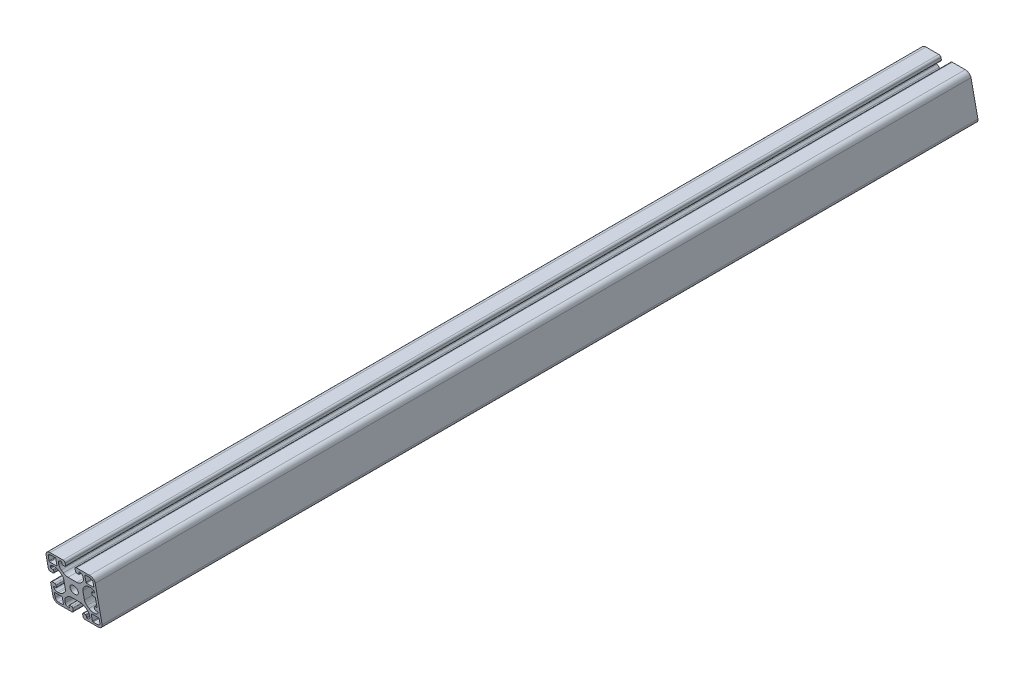
SolidWorks part; units mm, degrees
ref_plane "Piano frontale" through (0, 0, 0) normal (0, 0, 1) x (1, 0, 0)
ref_plane "Piano superiore" through (0, 0, 0) normal (0, 1, 0) x (1, 0, 0)
ref_plane "Piano destro" through (0, 0, 0) normal (1, 0, 0) x (0, 0, -1)
ref_plane "Piano1" through (0, 0, -340) normal (0, 0, -1) x (-1, 0, 0)
sketch "Schizzo1" plane through (0, 0, -340) normal (0, 0, -1) x (-1, 0, 0)
  line L0 (-12.3, -18.2) -> (-16, -18.2)
  line L1 (-18.2, -16) -> (-18.2, -12.3)
  line L2 (-17.7, -11.8) -> (-12.3, -11.8)
  line L3 (-11.8, -12.3) -> (-11.8, -17.7)
  line L4 (-11.8, 17.7) -> (-11.8, 12.3)
  line L5 (-12.3, 11.8) -> (-17.7, 11.8)
  line L6 (-18.2, 12.3) -> (-18.2, 16)
  line L7 (-16, 18.2) -> (-12.3, 18.2)
  line L8 (18.2, 16) -> (18.2, 12.3)
  line L9 (17.7, 11.8) -> (12.3, 11.8)
  line L10 (11.8, 12.3) -> (11.8, 17.7)
  line L11 (12.3, 18.2) -> (16, 18.2)
  line L12 (6.5, -15.5) -> (5, -15.5)
  line L13 (4, -16.5) -> (4, -18.5)
  line L14 (5.5, -20) -> (16, -20)
  line L15 (20, -16) -> (20, -5.5)
  line L16 (18.5, -4) -> (16.5, -4)
  line L17 (15.5, -5) -> (15.5, -6.5)
  line L18 (16, -7) -> (17.55, -7)
  line L19 (18, -7.45) -> (18, -7.5)
  line L20 (15.5, -10) -> (14.1924, -10)
  line L21 (10.6569, -8.5355) -> (9.2145, -7.0931)
  line L22 (7.75, -3.5576) -> (7.75, 3.5576)
  line L23 (9.2145, 7.0931) -> (10.6569, 8.5355)
  line L24 (14.1924, 10) -> (15.5, 10)
  line L25 (18, 7.5) -> (18, 7.45)
  line L26 (17.55, 7) -> (16, 7)
  line L27 (15.5, 6.5) -> (15.5, 5)
  line L28 (16.5, 4) -> (18.5, 4)
  line L29 (20, 5.5) -> (20, 16)
  line L30 (16, 20) -> (5.5, 20)
  line L31 (4, 18.5) -> (4, 16.5)
  line L32 (5, 15.5) -> (6.5, 15.5)
  line L33 (7, 16) -> (7, 17.55)
  line L34 (7.45, 18) -> (7.5, 18)
  line L35 (10, 15.5) -> (10, 14.1924)
  line L36 (8.5355, 10.6569) -> (7.0931, 9.2145)
  line L37 (3.5576, 7.75) -> (-3.5576, 7.75)
  line L38 (-7.0931, 9.2145) -> (-8.5355, 10.6569)
  line L39 (-10, 14.1924) -> (-10, 15.5)
  line L40 (-7.5, 18) -> (-7.45, 18)
  line L41 (-7, 17.55) -> (-7, 16)
  line L42 (-6.5, 15.5) -> (-5, 15.5)
  line L43 (-4, 16.5) -> (-4, 18.5)
  line L44 (-5.5, 20) -> (-16, 20)
  line L45 (-20, 16) -> (-20, -16)
  line L46 (-16, -20) -> (-5.5, -20)
  line L47 (-4, -18.5) -> (-4, -16.5)
  line L48 (-5, -15.5) -> (-6.5, -15.5)
  line L49 (-7, -16) -> (-7, -17.55)
  line L50 (-7.45, -18) -> (-7.5, -18)
  line L51 (-10, -15.5) -> (-10, -14.1924)
  line L52 (-8.5355, -10.6569) -> (-7.0931, -9.2145)
  line L53 (-3.5576, -7.75) -> (3.5576, -7.75)
  line L54 (7.0931, -9.2145) -> (8.5355, -10.6569)
  line L55 (10, -14.1924) -> (10, -15.5)
  line L56 (7.5, -18) -> (7.45, -18)
  line L57 (7, -17.55) -> (7, -16)
  line L58 (18.2, -12.3) -> (18.2, -16)
  line L59 (16, -18.2) -> (12.3, -18.2)
  line L60 (11.8, -17.7) -> (11.8, -12.3)
  line L61 (12.3, -11.8) -> (17.7, -11.8)
  line L62 (-16, 7) -> (-17.5, 7)
  line L63 (-15.5, 10) -> (-14.1924, 10)
  line L64 (-10.6569, 8.5355) -> (-9.2145, 7.0931)
  line L65 (-7.75, 3.5576) -> (-7.75, -3.5576)
  line L66 (-9.2145, -7.0931) -> (-10.6569, -8.5355)
  line L67 (-14.1924, -10) -> (-15.5, -10)
  line L68 (-17.5, -7) -> (-16, -7)
  line L69 (-15.5, -6.5) -> (-15.5, -5)
  line L70 (-16.5, -4) -> (-17.5, -4)
  line L71 (-18, -3.5) -> (-18, 3.5)
  line L72 (-17.5, 4) -> (-16.5, 4)
  line L73 (-15.5, 5) -> (-15.5, 6.5)
  arc A0 (-16, -18.2) -> (-18.2, -16) centre (-16, -16) cw
  arc A1 (-18.2, -12.3) -> (-17.7, -11.8) centre (-17.7, -12.3) cw
  arc A2 (-12.3, -11.8) -> (-11.8, -12.3) centre (-12.3, -12.3) cw
  arc A3 (-11.8, -17.7) -> (-12.3, -18.2) centre (-12.3, -17.7) cw
  arc A4 (-12.3, 18.2) -> (-11.8, 17.7) centre (-12.3, 17.7) cw
  arc A5 (-11.8, 12.3) -> (-12.3, 11.8) centre (-12.3, 12.3) cw
  arc A6 (-17.7, 11.8) -> (-18.2, 12.3) centre (-17.7, 12.3) cw
  arc A7 (-18.2, 16) -> (-16, 18.2) centre (-16, 16) cw
  arc A8 (16, 18.2) -> (18.2, 16) centre (16, 16) cw
  arc A9 (18.2, 12.3) -> (17.7, 11.8) centre (17.7, 12.3) cw
  arc A10 (12.3, 11.8) -> (11.8, 12.3) centre (12.3, 12.3) cw
  arc A11 (11.8, 17.7) -> (12.3, 18.2) centre (12.3, 17.7) cw
  arc A12 (5, -15.5) -> (4, -16.5) centre (5, -16.5) ccw
  arc A13 (4, -18.5) -> (5.5, -20) centre (5.5, -18.5) ccw
  arc A14 (16, -20) -> (20, -16) centre (16, -16) ccw
  arc A15 (20, -5.5) -> (18.5, -4) centre (18.5, -5.5) ccw
  arc A16 (16.5, -4) -> (15.5, -5) centre (16.5, -5) ccw
  arc A17 (15.5, -6.5) -> (16, -7) centre (16, -6.5) ccw
  arc A18 (17.55, -7) -> (18, -7.45) centre (17.55, -7.45) cw
  arc A19 (18, -7.5) -> (15.5, -10) centre (15.5, -7.5) cw
  arc A20 (14.1924, -10) -> (10.6569, -8.5355) centre (14.1924, -5) cw
  arc A21 (9.2145, -7.0931) -> (7.75, -3.5576) centre (12.75, -3.5576) cw
  arc A22 (7.75, 3.5576) -> (9.2145, 7.0931) centre (12.75, 3.5576) cw
  arc A23 (10.6569, 8.5355) -> (14.1924, 10) centre (14.1924, 5) cw
  arc A24 (15.5, 10) -> (18, 7.5) centre (15.5, 7.5) cw
  arc A25 (18, 7.45) -> (17.55, 7) centre (17.55, 7.45) cw
  arc A26 (16, 7) -> (15.5, 6.5) centre (16, 6.5) ccw
  arc A27 (15.5, 5) -> (16.5, 4) centre (16.5, 5) ccw
  arc A28 (18.5, 4) -> (20, 5.5) centre (18.5, 5.5) ccw
  arc A29 (20, 16) -> (16, 20) centre (16, 16) ccw
  arc A30 (5.5, 20) -> (4, 18.5) centre (5.5, 18.5) ccw
  arc A31 (4, 16.5) -> (5, 15.5) centre (5, 16.5) ccw
  arc A32 (6.5, 15.5) -> (7, 16) centre (6.5, 16) ccw
  arc A33 (7, 17.55) -> (7.45, 18) centre (7.45, 17.55) cw
  arc A34 (7.5, 18) -> (10, 15.5) centre (7.5, 15.5) cw
  arc A35 (10, 14.1924) -> (8.5355, 10.6569) centre (5, 14.1924) cw
  arc A36 (7.0931, 9.2145) -> (3.5576, 7.75) centre (3.5576, 12.75) cw
  arc A37 (-3.5576, 7.75) -> (-7.0931, 9.2145) centre (-3.5576, 12.75) cw
  arc A38 (-8.5355, 10.6569) -> (-10, 14.1924) centre (-5, 14.1924) cw
  arc A39 (-10, 15.5) -> (-7.5, 18) centre (-7.5, 15.5) cw
  arc A40 (-7.45, 18) -> (-7, 17.55) centre (-7.45, 17.55) cw
  arc A41 (-7, 16) -> (-6.5, 15.5) centre (-6.5, 16) ccw
  arc A42 (-5, 15.5) -> (-4, 16.5) centre (-5, 16.5) ccw
  arc A43 (-4, 18.5) -> (-5.5, 20) centre (-5.5, 18.5) ccw
  arc A44 (-16, 20) -> (-20, 16) centre (-16, 16) ccw
  arc A45 (-20, -16) -> (-16, -20) centre (-16, -16) ccw
  arc A46 (-5.5, -20) -> (-4, -18.5) centre (-5.5, -18.5) ccw
  arc A47 (-4, -16.5) -> (-5, -15.5) centre (-5, -16.5) ccw
  arc A48 (-6.5, -15.5) -> (-7, -16) centre (-6.5, -16) ccw
  arc A49 (-7, -17.55) -> (-7.45, -18) centre (-7.45, -17.55) cw
  arc A50 (-7.5, -18) -> (-10, -15.5) centre (-7.5, -15.5) cw
  arc A51 (-10, -14.1924) -> (-8.5355, -10.6569) centre (-5, -14.1924) cw
  arc A52 (-7.0931, -9.2145) -> (-3.5576, -7.75) centre (-3.5576, -12.75) cw
  arc A53 (3.5576, -7.75) -> (7.0931, -9.2145) centre (3.5576, -12.75) cw
  arc A54 (8.5355, -10.6569) -> (10, -14.1924) centre (5, -14.1924) cw
  arc A55 (10, -15.5) -> (7.5, -18) centre (7.5, -15.5) cw
  arc A56 (7.45, -18) -> (7, -17.55) centre (7.45, -17.55) cw
  arc A57 (7, -16) -> (6.5, -15.5) centre (6.5, -16) ccw
  arc A58 (17.7, -11.8) -> (18.2, -12.3) centre (17.7, -12.3) cw
  arc A59 (18.2, -16) -> (16, -18.2) centre (16, -16) cw
  arc A60 (12.3, -18.2) -> (11.8, -17.7) centre (12.3, -17.7) cw
  arc A61 (11.8, -12.3) -> (12.3, -11.8) centre (12.3, -12.3) cw
  circle A62 centre (0, 0) radius 3.4
  arc A63 (-15.5, 6.5) -> (-16, 7) centre (-16, 6.5) ccw
  arc A64 (-17.5, 7) -> (-18, 7.5) centre (-17.5, 7.5) cw
  arc A65 (-18, 7.5) -> (-15.5, 10) centre (-15.5, 7.5) cw
  arc A66 (-14.1924, 10) -> (-10.6569, 8.5355) centre (-14.1924, 5) cw
  arc A67 (-9.2145, 7.0931) -> (-7.75, 3.5576) centre (-12.75, 3.5576) cw
  arc A68 (-7.75, -3.5576) -> (-9.2145, -7.0931) centre (-12.75, -3.5576) cw
  arc A69 (-10.6569, -8.5355) -> (-14.1924, -10) centre (-14.1924, -5) cw
  arc A70 (-15.5, -10) -> (-18, -7.5) centre (-15.5, -7.5) cw
  arc A71 (-18, -7.5) -> (-17.5, -7) centre (-17.5, -7.5) cw
  arc A72 (-16, -7) -> (-15.5, -6.5) centre (-16, -6.5) ccw
  arc A73 (-15.5, -5) -> (-16.5, -4) centre (-16.5, -5) ccw
  arc A74 (-17.5, -4) -> (-18, -3.5) centre (-17.5, -3.5) cw
  arc A75 (-18, 3.5) -> (-17.5, 4) centre (-17.5, 3.5) cw
  arc A76 (-16.5, 4) -> (-15.5, 5) centre (-16.5, 5) ccw
extrude "Estrusione-Estrusione1" add sketch "Schizzo1" against normal blind 720
sketch "Schizzo9" plane through (20, 0, 0) normal (1, 0, 0) x (0, 0, -1)
  line L0 (340, -16) -> (340, 16) construction
  line L1 (-380, 16) -> (-380, -16) construction
  line L2 (340, 16) -> (340, 20) construction
  line L3 (340, 20) -> (-380, 20) construction
  line L4 (-380, 20) -> (-380, 16) construction
  line L5 (340, -20) -> (340, -16) construction
  line L6 (-380, -16) -> (-380, -20) construction
  line L7 (-380, -20) -> (340, -20) construction
  line L8 (340, -16) -> (340, 16)
  line L9 (-380, 16) -> (-380, -16)
  line L10 (340, 16) -> (340, 20)
  line L11 (340, 20) -> (-380, 20)
  line L12 (-380, 20) -> (-380, 16)
  line L13 (340, -20) -> (340, -16)
  line L14 (-380, -16) -> (-380, -20)
  line L15 (-380, -20) -> (340, -20)
  line L16 (-380, 20) -> (-372.9433, -20)
  line L18 (316.8895, -20) -> (316.8895, 20)
  line L19 (340, -20) -> (332.9469, 20)
extrude "Taglio-Estrusione1" cut sketch "Schizzo9" against normal through all
